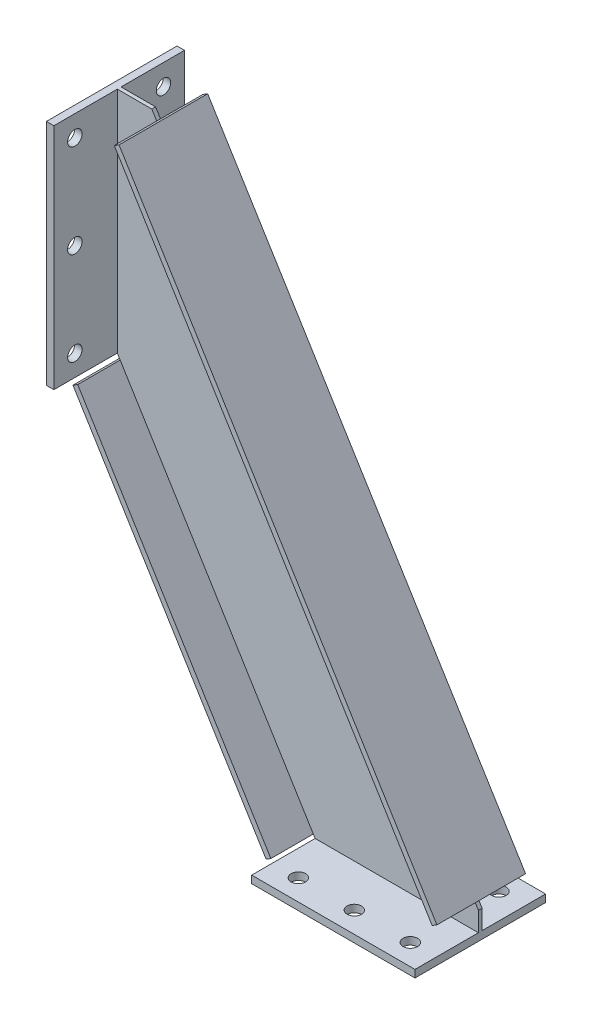
SolidWorks part; units mm, degrees
ref_plane "前视基准面" through (0, 0, 0) normal (0, 0, 1) x (1, 0, 0)
ref_plane "上视基准面" through (0, 0, 0) normal (0, 1, 0) x (1, 0, 0)
ref_plane "右视基准面" through (0, 0, 0) normal (1, 0, 0) x (0, 0, -1)
sketch "草图1" plane through (0, 0, 0) normal (0, 0, 1) x (1, 0, 0)
  line L1 (-300, -500) -> (474, -500)
  line L2 (-300, -500) -> (-300, 679)
  line L3 (-300, 679) -> (474, 679)
  line L4 (474, -500) -> (474, 679)
  point P0 (0, 0)
  dimension "D1" = 1179
  dimension "D2" = 774
  dimension "D3" = 300
  dimension "D4" = 500
extrude "拉伸1" add sketch "草图1" along normal mid plane 8
sketch "草图2" plane through (0, 0, 4) normal (0, 0, 1) x (1, 0, 0)
  line L0 (-300, -500) -> (-300, 189)
  line L1 (-300, 679) -> (-300, -500) construction
  line L2 (-300, -500) -> (124, -500)
  line L3 (-300, -500) -> (474, -500) construction
  line L4 (-300, 189) -> (124, -500)
  line L5 (-226, 679) -> (474, -458.5)
  line L6 (474, 679) -> (-300, 679) construction
  line L7 (474, -500) -> (474, 679) construction
  line L8 (-226, 679) -> (474, 679)
  line L9 (474, 679) -> (474, -458.5)
  dimension "D1" = 689
  dimension "D2" = 424
  dimension "D3" = 350
  dimension "D4" = 700
extrude "拉伸2" cut sketch "草图2" against normal blind 8
sketch "草图3" plane through (-300, 0, 0) normal (-1, 0, 0) x (0, 0, 1)
  line L0 (-140, 679) -> (140, 679)
  line L1 (140, 679) -> (140, 189)
  line L2 (140, 189) -> (-140, 189)
  line L3 (-140, 189) -> (-140, 679)
  line L4 (0, -1000) -> (0, 49000) construction
  dimension "D1" = 140
  dimension "D2" = 140
  dimension "D3" = 490
extrude "拉伸3" add sketch "草图3" along normal blind 16
sketch "草图4" plane through (-316, 0, 0) normal (-1, 0, 0) x (0, 0, 1)
  line L0 (0, -1000) -> (0, 49000) construction
  line L1 (140, 679) -> (-140, 679) construction
  line L2 (-95, 634) -> (-95, 434) construction
  line L3 (-140, 189) -> (140, 189) construction
  circle A0 centre (-95, 634) radius 15.5
  circle A1 centre (-95, 434) radius 15.5
  circle A2 centre (-95, 234) radius 15.5
  circle A3 centre (95, 234) radius 15.5
  circle A4 centre (95, 434) radius 15.5
  circle A5 centre (95, 634) radius 15.5
  dimension "D1" = 31
  dimension "D2" = 45
  dimension "D3" = 95
  dimension "D4" = 200
  dimension "D5" = 45
extrude "拉伸4" cut sketch "草图4" against normal blind 16
sketch "草图5" plane through (-133.2361, -81.9914, 0) normal (-0.8517, -0.5241, 0) x (0, 0, 1)
  line L0 (0, -1000) -> (0, 49000) construction
  line L1 (0, 306.5782) -> (95, 306.5782)
  line L2 (95, 306.5782) -> (95, -483.4218)
  line L3 (95, -483.4218) -> (-95, -483.4218)
  line L4 (-95, -483.4218) -> (-95, 306.5782)
  line L5 (-95, 306.5782) -> (0, 306.5782)
  line L6 (-140, 326.5782) -> (140, 326.5782) construction
  dimension "D1" = 190
  dimension "D2" = 790
  dimension "D3" = 20
extrude "拉伸5" add sketch "草图5" along normal blind 12
sketch "草图7" plane through (0, -500, 0) normal (0, -1, 0) x (1, 0, 0)
  line L0 (-1000, 0) -> (49000, 0) construction
  line L1 (124, 140) -> (124, -140)
  line L2 (124, -140) -> (474, -140)
  line L3 (474, -140) -> (474, 140)
  line L4 (474, 140) -> (124, 140)
  dimension "D1" = 350
  dimension "D2" = 140
extrude "拉伸6" add sketch "草图7" along normal blind 16
sketch "草图8" plane through (0, -516, 0) normal (0, -1, 0) x (1, 0, 0)
  line L0 (-1000, 0) -> (49000, 0) construction
  line L1 (124, 140) -> (124, -140) construction
  line L2 (179, 95) -> (299, 95) construction
  circle A0 centre (179, 95) radius 15.5
  circle A1 centre (299, 95) radius 15.5
  circle A2 centre (419, 95) radius 15.5
  circle A3 centre (419, -95) radius 15.5
  circle A4 centre (299, -95) radius 15.5
  circle A5 centre (179, -95) radius 15.5
  dimension "D1" = 31
  dimension "D2" = 95
  dimension "D3" = 55
  dimension "D4" = 120
extrude "拉伸7" cut sketch "草图8" against normal blind 16
sketch "草图9" plane through (139.1502, 85.6309, 0) normal (0.8517, 0.5241, 0) x (0, 0, -1)
  line L0 (0, -1000) -> (0, 49000) construction
  line L1 (-95, 676.722) -> (95, 676.722)
  line L2 (95, 676.722) -> (95, -623.278)
  line L3 (95, -623.278) -> (-95, -623.278)
  line L4 (-95, -623.278) -> (-95, 676.722)
  dimension "D1" = 95
  dimension "D2" = 1300
  dimension "D3" = 20
extrude "拉伸8" add sketch "草图9" along normal blind 12
